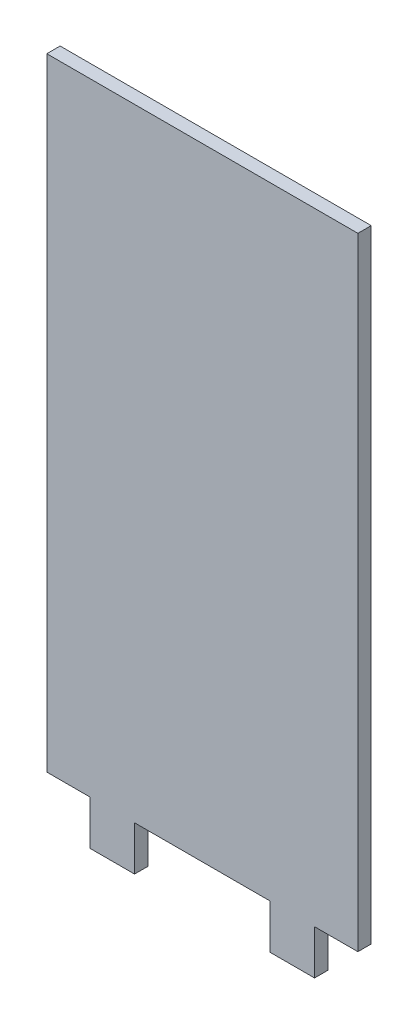
SolidWorks part; units mm, degrees
material "Glas"
ref_plane "Ebene vorne" through (0, 0, 0) normal (0, 0, 1) x (1, 0, 0)
ref_plane "Ebene oben" through (0, 0, 0) normal (0, 1, 0) x (1, 0, 0)
ref_plane "Ebene rechts" through (0, 0, 0) normal (1, 0, 0) x (0, 0, -1)
sketch "Skizze1" plane through (0, 0, 0) normal (0, 0, 1) x (1, 0, 0)
  line L1 (0, 0) -> (35, 0)
  line L2 (0, 0) -> (0, 75)
  line L3 (0, 75) -> (35, 75)
  line L4 (35, 0) -> (35, 75)
  dimension "D1" = 35
  dimension "D2" = 75
extrude "Aufsatz-Linear austragen1" add sketch "Skizze1" along normal blind 1.5
sketch "Skizze3" plane through (0, 0, 1.5) normal (0, 0, 1) x (1, 0, 0)
  line L0 (0, 0) -> (35, 0) construction
  line L1 (9.875, 0) -> (25.125, 0)
  line L2 (9.875, 0) -> (9.875, 5)
  line L3 (9.875, 5) -> (25.125, 5)
  line L4 (25.125, 0) -> (25.125, 5)
  line L5 (35, 0) -> (35, 75) construction
  line L6 (30.125, 5) -> (35, 5)
  line L7 (30.125, 5) -> (30.125, 0)
  line L8 (30.125, 0) -> (35, 0)
  line L9 (35, 5) -> (35, 0)
  line L10 (4.875, 5) -> (0, 5)
  line L11 (4.875, 5) -> (4.875, 0)
  line L12 (4.875, 0) -> (0, 0)
  line L13 (0, 5) -> (0, 0)
  dimension "D1" = 4.875
  dimension "D2" = 4.875
  dimension "D3" = 0
  dimension "D4" = 5
  dimension "D5" = 5
  dimension "D6" = 5
  dimension "D7" = 5
extrude "Schnitt-Linear austragen12" cut sketch "Skizze3" against normal blind 20
